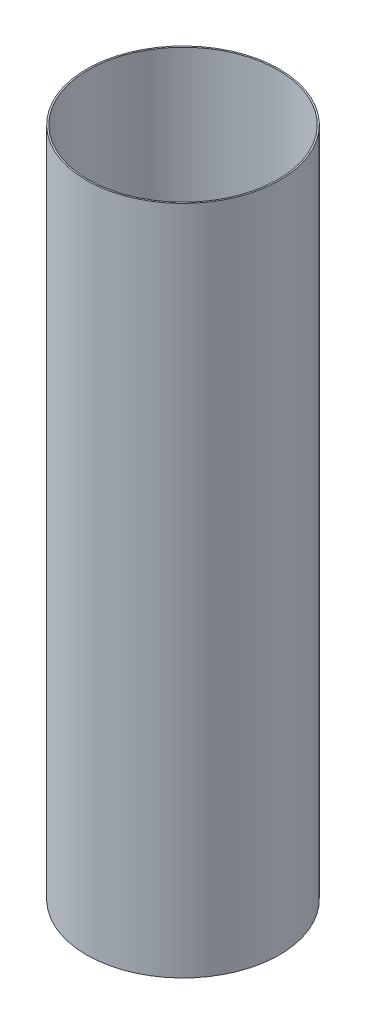
SolidWorks part; units mm, degrees
material "LE Phenolic"
ref_plane "Front Plane" through (0, 0, 0) normal (0, 0, 1) x (1, 0, 0)
ref_plane "Top Plane" through (0, 0, 0) normal (0, 1, 0) x (1, 0, 0)
ref_plane "Right Plane" through (0, 0, 0) normal (1, 0, 0) x (0, 0, -1)
sketch "Sketch1" plane through (0, 0, 0) normal (0, 1, 0) x (1, 0, 0)
  circle A0 centre (0, 0) radius 65.7225
  circle A1 centre (0, 0) radius 64.7065
  dimension "D1" = 131.445
  dimension "D2" = 129.413
extrude "Boss-Extrude1" add sketch "Sketch1" along normal blind 457.2
